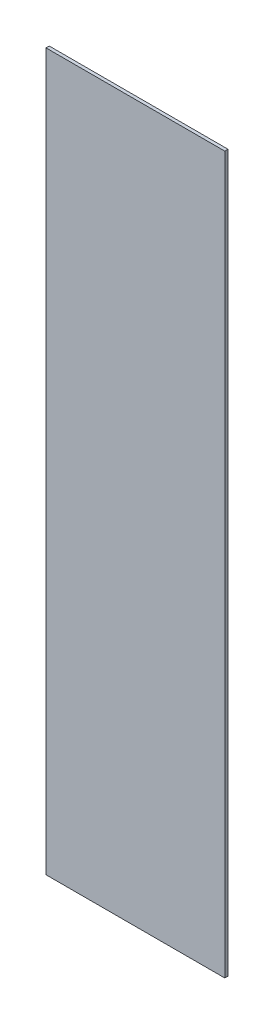
SolidWorks part; units mm, degrees
material "Solar panel smeared v5"
ref_plane "Front Plane" through (0, 0, 0) normal (0, 0, 1) x (1, 0, 0)
ref_plane "Top Plane" through (0, 0, 0) normal (0, 1, 0) x (1, 0, 0)
ref_plane "Right Plane" through (0, 0, 0) normal (1, 0, 0) x (0, 0, -1)
sketch "Body sketch" plane through (0, 0, 0) normal (0, 0, 1) x (1, 0, 0)
  line L1 (0, 0) -> (83, 0)
  line L2 (0, 0) -> (0, 332.5)
  line L3 (0, 332.5) -> (83, 332.5)
  line L4 (83, 0) -> (83, 332.5)
extrude "Body" add sketch "Body sketch" along normal blind 1.5
